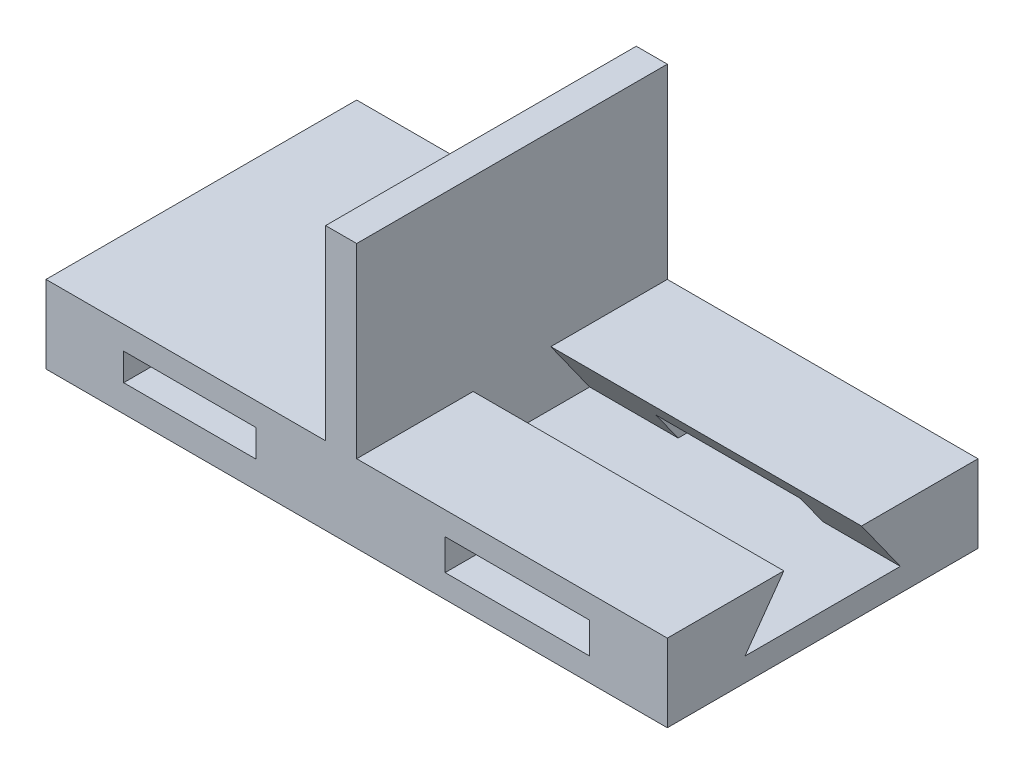
SolidWorks part; units mm, degrees
ref_plane "Front Plane" through (0, 0, 0) normal (0, 0, 1) x (1, 0, 0)
ref_plane "Top Plane" through (0, 0, 0) normal (0, 1, 0) x (1, 0, 0)
ref_plane "Right Plane" through (0, 0, 0) normal (1, 0, 0) x (0, 0, -1)
sketch "Sketch3" plane through (0, 0, 0) normal (1, 0, 0) x (0, 0, -1)
  line L1 (0, 0) -> (20, 0)
  line L2 (0, 0) -> (0, -12)
  line L3 (0, -12) -> (20, -12)
  line L4 (20, 0) -> (20, -12)
  dimension "D1" = 20
  dimension "D2" = 12
extrude "Boss-Extrude3" add sketch "Sketch3" along normal blind 2
sketch "Sketch4" plane through (2, 0, 0) normal (1, 0, 0) x (0, 0, -1)
  line L0 (0, -12) -> (20, -12) construction
  line L6 (0, -12) -> (20, -12)
  line L8 (0, -12) -> (0, -17)
  line L9 (0, -17) -> (20, -17)
  line L10 (20, -12) -> (20, -17)
  dimension "D1" = 20
  dimension "D4" = 5
extrude "Boss-Extrude5" add sketch "Sketch4" along normal blind 20 and the other way blind 20
sketch "Sketch6" plane through (22, 0, 0) normal (1, 0, 0) x (0, 0, -1)
  line L0 (10, -12) -> (10, -17) construction
  line L1 (20, -12) -> (0, -12) construction
  line L2 (0, -17) -> (20, -17) construction
  line L3 (7.5, -12) -> (12.5, -12)
  line L4 (5, -15.5) -> (15, -15.5)
  line L5 (7.5, -12) -> (5, -15.5)
  line L6 (15, -15.5) -> (12.5, -12)
  point P9 (10, -12)
  point P12 (10, -15.5)
  dimension "D1" = 5
  dimension "D2" = 2.5
  dimension "D3" = 10
  dimension "D4" = 3.5
extrude "Cut-Extrude1" cut sketch "Sketch6" against normal blind 20
sketch "Sketch7" plane through (0, 0, -20) normal (0, 0, -1) x (-1, 0, 0)
  line L0 (-22, -17) -> (-22, -12) construction
  line L1 (4.4878, -13.5) -> (13, -13.5)
  line L2 (4.4878, -13.5) -> (4.4878, -15.2611)
  line L3 (4.4878, -15.2611) -> (13, -15.2611)
  line L4 (13, -13.5) -> (13, -15.2611)
  line L5 (-7.6953, -13.5) -> (-17, -13.5)
  line L6 (-7.6953, -13.5) -> (-7.6953, -15.5)
  line L7 (-7.6953, -15.5) -> (-17, -15.5)
  line L8 (-17, -13.5) -> (-17, -15.5)
  line L9 (18, -17) -> (18, -12) construction
  line L10 (-2, -12) -> (-22, -12) construction
  line L11 (18, -12) -> (0, -12) construction
  dimension "D1" = 2
  dimension "D2" = 5
  dimension "D3" = 5
  dimension "D4" = 1.5
  dimension "D5" = 1.5
extrude "Cut-Extrude2" cut sketch "Sketch7" against normal through all
